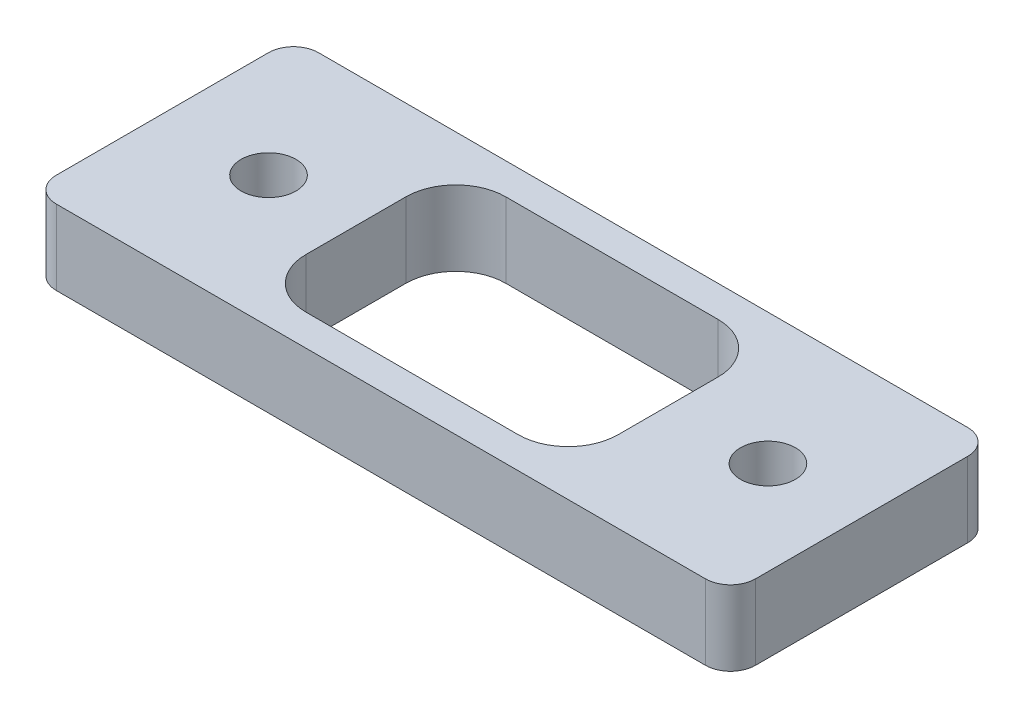
SolidWorks part; units mm, degrees
ref_plane "前视基准面" through (0, 0, 0) normal (0, 0, 1) x (1, 0, 0)
ref_plane "上视基准面" through (0, 0, 0) normal (0, 1, 0) x (1, 0, 0)
ref_plane "右视基准面" through (0, 0, 0) normal (1, 0, 0) x (0, 0, -1)
other "Configuration Table"
sketch "草图1" plane through (0, 0, 0) normal (0, 0, 1) x (1, 0, 0)
  line L0 (28, 0) -> (28, -12) construction
  line L1 (0, 0) -> (56, 0)
  line L2 (0, 0) -> (0, -12)
  line L3 (0, -12) -> (56, -12)
  line L4 (56, 0) -> (56, -12)
  line L5 (-13, -12) -> (69, -12)
  line L6 (-13, -12) -> (-13, -63)
  line L7 (-13, -63) -> (69, -63)
  line L8 (69, -12) -> (69, -63)
  dimension "D1" = 12
  dimension "D2" = 56
  dimension "D3" = 82
  dimension "D4" = 51
extrude "凸台-拉伸1" add sketch "草图1" along normal blind 21 contours L8 L5 L3 L6 L7 | L1 L0 L5 L4 | L0 L1 L2 L3
sketch "草图2" plane through (0, 0, 0) normal (0, 0, -1) x (-1, 0, 0)
  line L0 (-69, -37.5) -> (13, -37.5) construction
  line L1 (-28, 0) -> (-28, -63) construction
  line L8 (-69, -12) -> (-69, -63)
  line L9 (-69, -63) -> (13, -63)
  line L10 (13, -63) -> (13, -12)
  line L11 (13, -12) -> (0, -12)
  line L12 (0, -12) -> (0, 0)
  line L13 (0, 0) -> (-56, 0)
  line L14 (-56, 0) -> (-56, -12)
  line L15 (-56, -12) -> (-69, -12)
  line L16 (-69, -12) -> (-69, -63)
  line L17 (-69, -63) -> (13, -63)
  line L18 (13, -63) -> (13, -12)
  line L19 (13, -12) -> (0, -12)
  line L20 (0, -12) -> (0, 0)
  line L21 (0, 0) -> (-56, 0)
  line L22 (-56, 0) -> (-56, -12)
  line L23 (-56, -12) -> (-69, -12)
  circle A0 centre (-47, -2.75) radius 1.75
  circle A1 centre (-9, -2.75) radius 1.75
  circle A2 centre (-58, -54.25) radius 1.75
  circle A3 centre (2, -54.25) radius 1.75
  point P21 (-47, -1)
  dimension "D2" = 3.5
  dimension "D7" = 3.5
  dimension "D3" = 38
  dimension "D4" = 60
  dimension "D5" = 51.5
  dimension "D6" = 1
  dimension "D1" = 0
extrude "切除-拉伸1" cut sketch "草图2" against normal blind 59 contours A2 | A3
sketch "草图3" plane through (0, 0, 0) normal (0, 1, 0) x (1, 0, 0)
  line L0 (-13, -10.5) -> (69, -10.5) construction
  line L1 (-13, -21) -> (-13, 0) construction
  line L2 (69, -21) -> (69, 0) construction
  circle A0 centre (48.5, -10.5) radius 2.2
  circle A1 centre (8.5, -10.5) radius 2.2
  dimension "D1" = 20.5
  dimension "D2" = 40
  dimension "D3" = 4.4
extrude "切除-拉伸2" cut sketch "草图3" against normal blind 65
sketch "草图4" plane through (0, 0, 0) normal (0, 0, -1) x (-1, 0, 0)
  line L0 (-28, 0) -> (-28, -63) construction
  line L1 (-50.5, -7) -> (-50.5, -11)
  line L2 (-5.5, -7) -> (-5.5, -11)
  line L3 (-50.5, -7) -> (-53.5, -7)
  line L4 (-53.5, -7) -> (-53.5, -11)
  line L5 (-53.5, -11) -> (-50.5, -11)
  line L6 (-5.5, -7) -> (-2.5, -7)
  line L7 (-2.5, -7) -> (-2.5, -11)
  line L8 (-69, -12) -> (-69, -63)
  line L9 (-69, -63) -> (13, -63)
  line L10 (13, -63) -> (13, -12)
  line L11 (13, -12) -> (0, -12)
  line L12 (0, -12) -> (0, 0)
  line L13 (0, 0) -> (-56, 0)
  line L14 (-56, 0) -> (-56, -12)
  line L15 (-56, -12) -> (-69, -12)
  line L16 (-69, -12) -> (-69, -63)
  line L17 (-69, -63) -> (13, -63)
  line L18 (13, -63) -> (13, -12)
  line L19 (13, -12) -> (0, -12)
  line L20 (0, -12) -> (0, 0)
  line L21 (0, 0) -> (-56, 0)
  line L22 (-56, 0) -> (-56, -12)
  line L23 (-56, -12) -> (-69, -12)
  line L24 (-2.5, -11) -> (-5.5, -11)
  circle A1 centre (-9, -2.75) radius 1.75
  circle A2 centre (-9, -2.75) radius 1.75
  circle A3 centre (-47, -2.75) radius 1.75
  circle A4 centre (-47, -2.75) radius 1.75
  circle A5 centre (2, -54.25) radius 1.75
  circle A6 centre (2, -54.25) radius 1.75
  circle A7 centre (-58, -54.25) radius 1.75
  circle A8 centre (-58, -54.25) radius 1.75
  point P23 (-28, -63)
  dimension "D6" = 45
  dimension "D7" = 4
  dimension "D8" = 4
  dimension "D9" = 3
  dimension "D10" = 1
  dimension "D11" = 3
  dimension "D1" = 0
  dimension "D2" = 0
  dimension "D3" = 0
  dimension "D4" = 0
  dimension "D5" = 0
sketch "草图7" plane through (69, 0, 0) normal (1, 0, 0) x (0, 0, -1)
  line L0 (-21, -19.5) -> (0, -19.5) construction
  line L1 (-21, -12) -> (-21, -63) construction
  line L2 (0, -12) -> (0, -63) construction
  line L3 (-10.5, 0) -> (-10.5, -63) construction
  line L4 (-21, 0) -> (0, 0) construction
  line L5 (-21, -63) -> (0, -63) construction
  line L6 (-21, -12) -> (0, -12) construction
  line L7 (-18, -12) -> (-3, -12)
  line L8 (-18, -12) -> (-18, -27)
  line L9 (-18, -27) -> (-3, -27)
  line L10 (-3, -12) -> (-3, -27)
  dimension "D2" = 15
  dimension "D3" = 15
extrude "切除-拉伸3" cut sketch "草图7" against normal blind 109
sketch "草图9" plane through (56, 0, 0) normal (1, 0, 0) x (0, 0, -1)
  line L8 (-18, -27) -> (-18, -12)
  line L9 (-18, -27) -> (-18, -12)
  line L10 (-21, -12) -> (-21, -63)
  line L11 (-21, -63) -> (0, -63)
  line L12 (0, -63) -> (0, -12)
  line L13 (-18, -12) -> (-21, -12)
  line L14 (-18, -12) -> (-21, -12)
  line L15 (-3, -27) -> (-18, -27)
  line L18 (-21, -12) -> (-21, -63)
  line L19 (-21, -63) -> (0, -63)
  line L20 (0, -63) -> (0, -12)
  line L23 (-3, -27) -> (-18, -27)
  line L24 (0, -12) -> (-3, -12)
  line L25 (0, -12) -> (-3, -12)
  line L26 (-3, -12) -> (-3, -27)
  line L27 (-3, -12) -> (-3, -27)
  dimension "D1" = 0
extrude "切除-拉伸5" cut sketch "草图9" against normal mid plane 168
sketch "草图12" plane through (0, 0, 21) normal (0, 0, 1) x (1, 0, 0)
  line L4 (0, -12) -> (56, -12)
  line L5 (56, -12) -> (56, 0)
  line L7 (0, 0) -> (0, -12)
  line L8 (0, -12) -> (56, -12)
  line L11 (0, 0) -> (0, -12)
  line L12 (56, -12) -> (56, 0)
  line L14 (56, 0) -> (0, 0)
  line L15 (56, 0) -> (0, 0)
  dimension "D1" = 0
sketch "草图13" plane through (0, 0, 0) normal (0, 1, 0) x (1, 0, 0)
  line L0 (28, 0) -> (28, -32) construction
  line L1 (0, 0) -> (56, 0) construction
  line L2 (10, 0) -> (10, -32)
  line L3 (46, 0) -> (46, -32)
  line L4 (56, 0) -> (0, 0)
  line L5 (0, 0) -> (0, -21)
  line L6 (0, -21) -> (56, -21)
  line L7 (56, -21) -> (56, 0)
  line L8 (56, 0) -> (0, 0)
  line L9 (0, 0) -> (0, -21)
  line L11 (56, -21) -> (56, 0)
  line L12 (20.5, -4) -> (20.5, -28)
  line L13 (14.5, -4) -> (41.5, -4)
  line L14 (14.5, -4) -> (14.5, -28)
  line L15 (14.5, -28) -> (41.5, -28)
  line L16 (41.5, -4) -> (41.5, -28)
  line L17 (22.5, -4) -> (22.5, -28)
  line L18 (33.5, -4) -> (33.5, -28)
  line L19 (35.5, -4) -> (35.5, -28)
  line L24 (0, -21) -> (56, -21)
  dimension "D2" = 36
  dimension "D3" = 4
  dimension "D5" = 27
  dimension "D6" = 2
  dimension "D7" = 2
  dimension "D8" = 11
  dimension "D1" = 0
fillet "圆角1" radius 2 4 edges at (56, -6, 0) (56, -6, 21) (0, -6, 0) (0, -6, 21)
sketch "草图14" plane through (0, 0, 0) normal (0, 1, 0) x (1, 0, 0)
  line L4 (56, -19) -> (56, -2)
  line L5 (54, 0) -> (2, 0)
  line L6 (0, -2) -> (0, -19)
  line L7 (2, -21) -> (54, -21)
  line L8 (56, -19) -> (56, -2)
  line L9 (54, 0) -> (2, 0)
  line L10 (0, -2) -> (0, -19)
  line L11 (2, -21) -> (54, -21)
  arc A4 (56, -2) -> (54, 0) centre (54, -2) ccw
  arc A5 (2, 0) -> (0, -2) centre (2, -2) ccw
  arc A6 (0, -19) -> (2, -21) centre (2, -19) ccw
  arc A7 (54, -21) -> (56, -19) centre (54, -19) ccw
  arc A8 (56, -2) -> (54, 0) centre (54, -2) ccw
  arc A9 (2, 0) -> (0, -2) centre (2, -2) ccw
  arc A10 (0, -19) -> (2, -21) centre (2, -19) ccw
  arc A11 (54, -21) -> (56, -19) centre (54, -19) ccw
  dimension "D1" = 0
extrude "切除-拉伸6" cut sketch "草图14" against normal blind 6
sketch "草图15" plane through (0, -6, 0) normal (0, 1, 0) x (1, 0, 0)
  line L0 (28, 0) -> (28, -21) construction
  line L1 (54, 0) -> (2, 0) construction
  line L2 (2, -21) -> (54, -21) construction
  line L3 (0, -10.5) -> (56, -10.5) construction
  line L4 (0, -2) -> (0, -19) construction
  line L5 (56, -19) -> (56, -2) construction
  line L6 (54, 0) -> (2, 0)
  line L8 (15.5, -2.5) -> (40.5, -2.5)
  line L9 (15.5, -2.5) -> (15.5, -18.5)
  line L10 (15.5, -18.5) -> (40.5, -18.5)
  line L11 (40.5, -2.5) -> (40.5, -18.5)
  point P13 (28, 0)
  dimension "D1" = 25
  dimension "D2" = 16
extrude "切除-拉伸7" cut sketch "草图15" against normal blind 55 contours L11 L8 L9 L10
fillet "圆角2" radius 4 4 edges at (15.5, -9, 2.5) (15.5, -9, 18.5) (40.5, -9, 2.5) (40.5, -9, 18.5)
